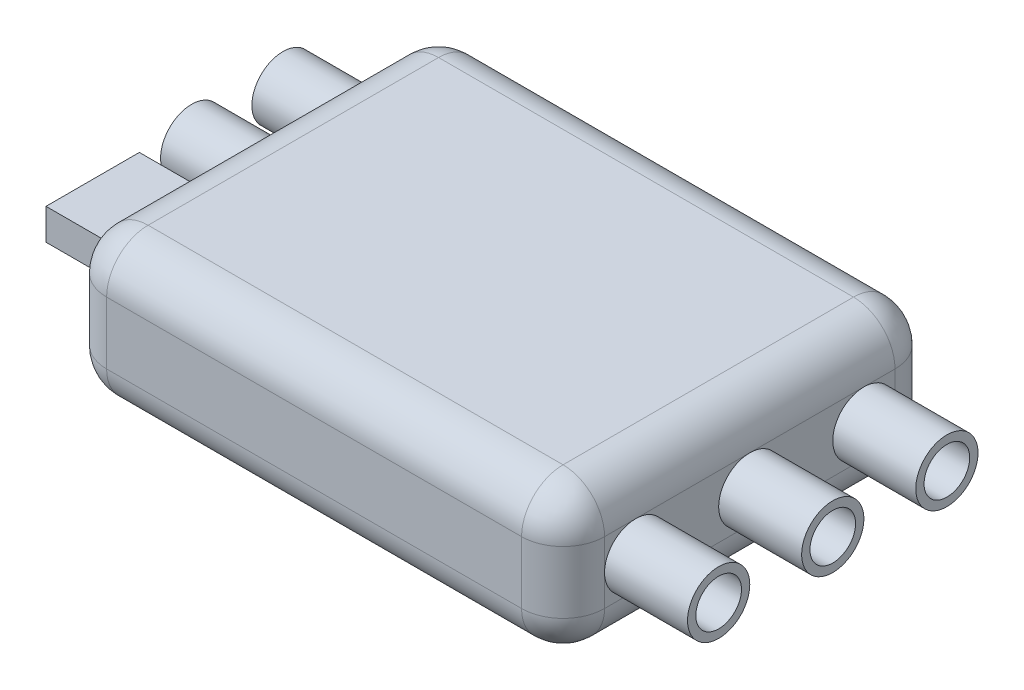
SolidWorks part; units mm, degrees
ref_plane "Front Plane" through (0, 0, 0) normal (0, 0, 1) x (1, 0, 0)
ref_plane "Top Plane" through (0, 0, 0) normal (0, 1, 0) x (1, 0, 0)
ref_plane "Right Plane" through (0, 0, 0) normal (1, 0, 0) x (0, 0, -1)
sketch "Sketch2" plane through (0, 0, 0) normal (0, 1, 0) x (1, 0, 0)
  line L1 (-10, 9) -> (10, 9)
  line L2 (-12, 7) -> (-12, -7)
  line L3 (-10, -9) -> (10, -9)
  line L4 (12, 7) -> (12, -7)
  line L5 (-12, 9) -> (12, -9) construction
  line L6 (-12, -9) -> (12, 9) construction
  arc A0 (10, 9) -> (12, 7) centre (10, 7) cw
  arc A1 (-12, -7) -> (-10, -9) centre (-10, -7) ccw
  arc A2 (-10, 9) -> (-12, 7) centre (-10, 7) ccw
  arc A3 (10, -9) -> (12, -7) centre (10, -7) ccw
  point P0 (0, 0)
  dimension "D3" = 2
  dimension "D1" = 24
  dimension "D2" = 18
extrude "Boss-Extrude1" add sketch "Sketch2" along normal blind 7
fillet "Fillet1" radius 2 16 edges at (0, 0, -9) (-11.4142, 0, -8.4142) (-12, 0, 0) (-11.4142, 0, 8.4142) (0, 0, 9) (11.4142, 0, 8.4142) (12, 0, 0) (11.4142, 0, -8.4142) (12, 7, 0) (11.4142, 7, 8.4142) (0, 7, 9) (-11.4142, 7, 8.4142) (-12, 7, 0) (-11.4142, 7, -8.4142) (0, 7, -9) (11.4142, 7, -8.4142)
sketch "Sketch3" plane through (12, 0, 0) normal (1, 0, 0) x (0, 0, -1)
  line L0 (-7, 3.5) -> (7, 3.5) construction
  line L1 (-7, 5) -> (-7, 2) construction
  line L2 (7, 5) -> (7, 2) construction
  circle A0 centre (0, 3.5) radius 1.5
  circle A1 centre (0, 3.5) radius 1.1
  circle A2 centre (-5.5, 3.5) radius 1.5
  circle A3 centre (5.5, 3.5) radius 1.5
  circle A4 centre (5.5, 3.5) radius 1.1
  circle A5 centre (-5.5, 3.5) radius 1.1
  dimension "D1" = 3
  dimension "D2" = 0.4
extrude "Boss-Extrude2" add sketch "Sketch3" along normal blind 4
sketch "Sketch4" plane through (-12, 0, 0) normal (-1, 0, 0) x (0, 0, 1)
  line L0 (-7, 3.5) -> (7, 3.5) construction
  line L1 (-7, 5) -> (-7, 2) construction
  line L2 (7, 5) -> (7, 2) construction
  line L4 (5.9218, 4.25) -> (1.4218, 4.25)
  line L5 (5.9218, 4.25) -> (5.9218, 2.75)
  line L6 (5.9218, 2.75) -> (1.4218, 2.75)
  line L7 (1.4218, 4.25) -> (1.4218, 2.75)
  circle A0 centre (-5.5, 3.5) radius 1.5
  circle A1 centre (-1.1, 3.5) radius 1.5
  circle A2 centre (-1.1, 3.5) radius 1.1
  circle A3 centre (-5.5, 3.5) radius 1.1
  dimension "D3" = 3
  dimension "D4" = 0.4
  dimension "D1" = 4.5
  dimension "D2" = 1.5
  dimension "D5" = 4.4
extrude "Boss-Extrude3" add sketch "Sketch4" along normal blind 4
